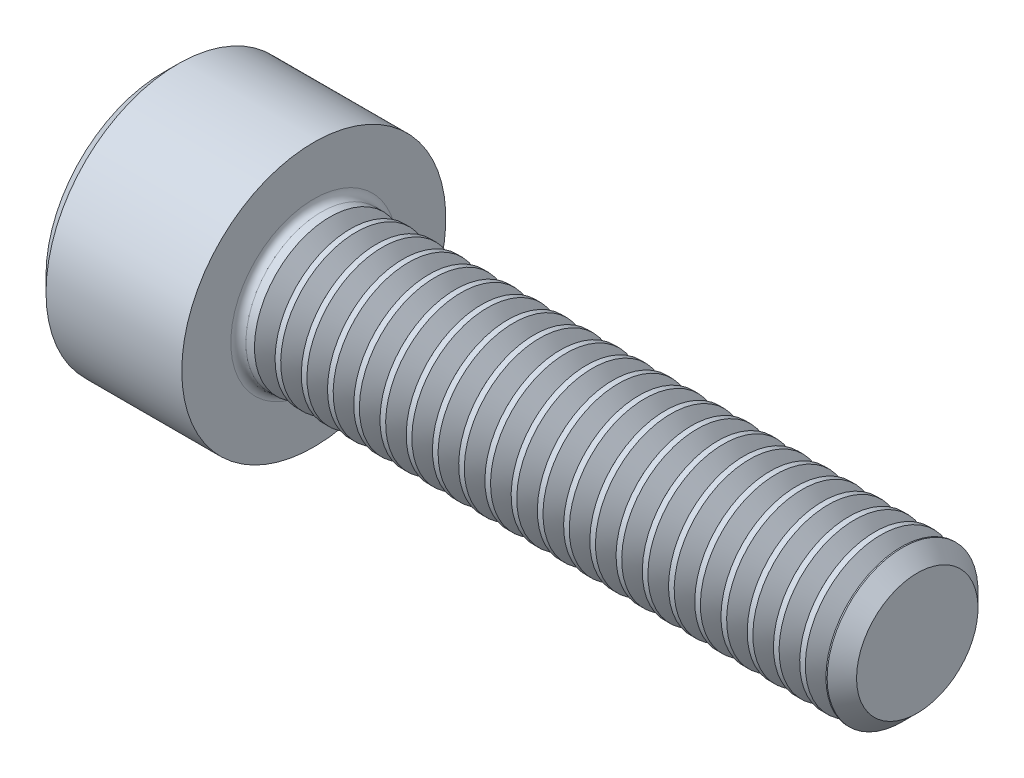
SolidWorks part; units mm, degrees
revolve "Base-Revolve" add sketch "BodySke"
sketch "BodySke" plane through (0, 0, 0) normal (0, 0, 1) x (1, 0, 0)
  line L0 (0, 0) -> (0, 3.1)
  line L1 (0.4, 3.5) -> (4, 3.5)
  line L2 (4, 3.5) -> (4, 2)
  line L3 (4, 2) -> (19.61, 2)
  line L4 (20, 1.61) -> (20, 0)
  line L5 (20, 0) -> (0, 0)
  line L6 (-31.75, 0) -> (127, 0) construction
  line L7 (0, 3.1) -> (0.4, 3.5)
  line L8 (20, 1.61) -> (19.61, 2)
  line L9 (0, -3.1) -> (0.4, -3.5) construction
  line L10 (20, -1.61) -> (19.61, -2) construction
  line L11 (4.7, 9.525) -> (4.7, 3.175) construction
  line L12 (4, 9.525) -> (4, 3.175) construction
  line L13 (-30, 9.525) -> (-30, 3.175) construction
  dimension "Diameter" = 4
  dimension "Head_ht" = 4
  dimension "Length" = 16
  dimension "Body_ch_ang" = 45
  dimension "Head_dia" = 7
  dimension "Head_ch_ang" = 45
  dimension "Minor_dia" = 3.22
  dimension "Advance" = 0.7
  dimension "Thread_nom" = 16
  dimension "Thread_length" = 50
  dimension "Head_ch_ht" = 0.4
cosmetic thread "ThreadCosmetic" [suppressed]
fillet "Fillet1" radius 0.2 1 edges at (4, 0, 2)
ref_plane "Plane1" through (0, 0, 0) normal (0, 0, 1) x (1, 0, 0)
ref_plane "Plane2" through (0, 0, 0) normal (0, 1, 0) x (1, 0, 0)
ref_plane "Plane3" through (0, 0, 0) normal (1, 0, 0) x (0, 0, -1)
sketch "Sketch2" plane through (0, 0, 0) normal (0, 0, 1) x (1, 0, 0)
  line L0 (0, 1.5355) -> (2, 1.5355)
  line L1 (2, 1.5355) -> (2.8865, 0)
  line L2 (-31.75, 0) -> (127, 0) construction
  line L3 (2.8865, 0) -> (0, 0)
  line L4 (0, 0) -> (0, 1.5355)
  line L5 (0, 3.1) -> (0, -3.1) construction
  line L6 (0, 0) -> (47.625, 0) construction
  line L7 (4, -3.5) -> (4, 3.5) construction
  dimension "D1" = 1.5355
  dimension "D2" = 60
revolve "Hex-PreBroach" cut sketch "Sketch2" angle 360 about L6
sketch "Sketch3" plane through (0, 0, 0) normal (-1, 0, 0) x (0, 0.5, 0.866)
  line L0 (0.8865, 1.5355) -> (-0.8865, 1.5355)
  line L1 (-0.8865, 1.5355) -> (-1.773, 0)
  line L2 (0.8865, 1.5355) -> (1.773, 0)
  line L3 (0.8865, -1.5355) -> (1.773, 0)
  line L4 (0.8865, -1.5355) -> (-0.8865, -1.5355)
  line L5 (-0.8865, -1.5355) -> (-1.773, 0)
  dimension "D1" = 1.5355
  dimension "D2" = 1.5355
  dimension "Hex_size" = 3.071
extrude "Hex" cut sketch "Sketch3" against normal blind 2
sketch "Sketch4" plane through (0, 0, 0) normal (-1, 0, 0) x (0, 0, 1)
  line L0 (0, 0) -> (1.7399, 0)
  line L1 (0, 0) -> (6.1484, 3.5498) construction
  line L2 (0, 0) -> (0.8699, 1.5068)
  line L3 (1.4457, 0.3947) -> (1.6607, 0.5189)
  line L4 (1.0647, 1.0546) -> (1.2797, 1.1788)
  arc A0 (1.4457, 0.3947) -> (1.0647, 1.0546) centre (0, 0) ccw
  arc A1 (1.7399, 0) -> (1.6607, 0.5189) centre (0, 0) ccw
  arc A2 (0.8699, 1.5068) -> (1.2797, 1.1788) centre (0, 0) cw
  dimension "D1" = 30
  dimension "D2" = 60
  dimension "Spline_p_dim" = 0.762
  dimension "D3" = 0.381
extrude "Spline" [suppressed] cut sketch "Sketch4" against normal blind 2
pattern_circular "CirPattern1" [suppressed] count 6 every 60
sketch "Sketch5" plane through (0, 0, 0) normal (0, 0, 1) x (1, 0, 0)
  line L0 (-31.75, 0) -> (127, 0) construction
  line L2 (0, 3.1) -> (0, -3.1) construction
  circle A0 centre (1.6, 0) radius 0.675
  dimension "Drilled_hole_dia" = 1.35
  dimension "Drilled_hole_loc" = 1.6
extrude "Hole" [suppressed] cut sketch "Sketch5" against normal through all and the other way through all
pattern_circular "Drilled-4" [suppressed] count 2 every 60
pattern_circular "Drilled-6" [suppressed] count 3 every 60
sketch "ThdSchSke" plane through (0, 0, 0) normal (0, 0, 1) x (1, 0, 0)
  line L0 (4.7, -1.61) -> (4.4269, -2)
  line L1 (4.7, -1.61) -> (4.9731, -2)
  line L2 (4.9731, -2) -> (4.9731, -2.5)
  line L3 (-3.175, 0) -> (5.1513, 0) construction
  line L5 (4.9731, -2.5) -> (4.4269, -2.5)
  line L6 (4.4269, -2.5) -> (4.4269, -2)
  line L7 (0, 3.1) -> (0, -3.1) construction
  dimension "Thread_minor" = 3.22
  dimension "Diameter" = 4
  dimension "Start" = 4.7
revolve "ThreadSchematic" cut sketch "ThdSchSke" angle 360 about L3
pattern_linear "ThdSchPat" count 22 spacing 0.6955 along (1, 0, 0) of "ThreadSchematic"
equation "\"D2@Sketch3\" = \"Hex_size@Sketch3\" / 2"
equation "\"D1@Sketch3\" = \"Hex_size@Sketch3\" / 2"
equation "\"D1@Sketch2\" = \"Hex_size@Sketch3\" / 2"
equation "\"D3@Sketch4\" = \"Spline_p_dim@Sketch4\" / 2"
equation "\"Thread_minor@ThreadCosmetic\"  =  \"Minor_dia@BodySke\""
equation "\"D2@CirPattern1\" = 360 / \"Num_teeth@CirPattern1\""
equation "\"Wall_thickness@Sketch2\" = \"Head_ht@BodySke\" - \"Key_eng@Hex\""
equation "\"Thread_length@ThreadCosmetic\" = ((sgn( (\"Length@BodySke\" - \"Advance@BodySke\" ) - \"Thread_nom@BodySke\" )-1)*( (\"Length@BodySke\" - \"Advance@BodySke\" ) - \"Thread_nom@BodySke\" ))/-2+ \"Thread_nom@BodySke\""
equation "\"Thread_minor@ThdSchSke\" = \"Minor_dia@BodySke\""
equation "\"Diameter@ThdSchSke\" = \"Diameter@BodySke\""
equation "\"Overcut@ThdSchSke\" = \"Diameter@BodySke\" * 1.25"
equation "\"Start@ThdSchSke\" = \"Head_ht@BodySke\" + \"Length@BodySke\" - \"Thread_length@ThreadCosmetic\"  '---Non-countersunk---"
equation "\"Num_threads@ThdSchPat\" = int( \"Thread_length@ThreadCosmetic\" / \"Advance@BodySke\" + 0.999 )  + 1"
equation "\"Advance@ThdSchPat\" = \"Thread_length@ThreadCosmetic\" /  (\"Num_threads@ThdSchPat\" - 1) 'relax it"
equation "\"Num_threads@ThdSchPat\" = \"Num_threads@ThdSchPat\" - sgn( \"Num_threads@ThdSchPat\" - 1) '---chamfered tips only---"
